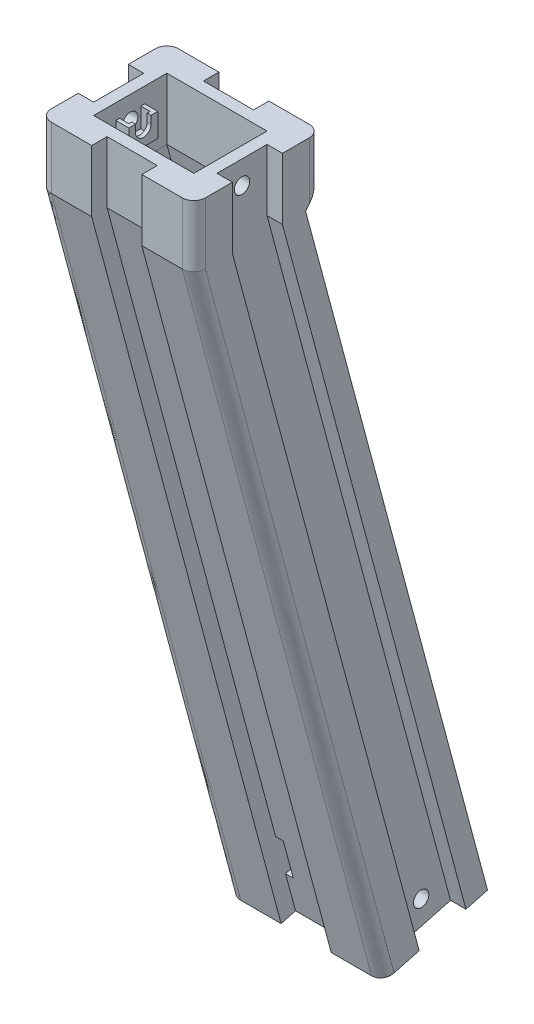
SolidWorks part; units mm, degrees
ref_plane "Front Plane" through (0, 0, 0) normal (0, 0, 1) x (1, 0, 0)
ref_plane "Top Plane" through (0, 0, 0) normal (0, 1, 0) x (1, 0, 0)
ref_plane "Right Plane" through (0, 0, 0) normal (1, 0, 0) x (0, 0, -1)
sketch "Sketch2" plane through (0, 0, 0) normal (0, 1, 0) x (1, 0, 0)
  line L0 (0, 0) -> (0, 33) construction
  line L1 (0, 33) -> (-17, 33)
  line L2 (-20, 30) -> (-20, 3)
  line L3 (-17, 0) -> (0, 0)
  line L4 (-20, 16.5) -> (0, 16.5) construction
  line L5 (0, 33) -> (17, 33)
  line L6 (20, 30) -> (20, 3)
  line L7 (17, 0) -> (0, 0)
  arc A0 (-17, 33) -> (-20, 30) centre (-17, 30) ccw
  arc A1 (-20, 3) -> (-17, 0) centre (-17, 3) ccw
  arc A2 (17, 33) -> (20, 30) centre (17, 30) cw
  arc A3 (20, 3) -> (17, 0) centre (17, 3) cw
  dimension "D3" = 3
  dimension "D1" = 20
  dimension "D2" = 33
extrude "Boss-Extrude1" add sketch "Sketch2" along normal blind 16
sketch "Sketch3" plane through (20, 0, 0) normal (1, 0, 0) x (0, 0, -1)
  line L0 (16.5, 0) -> (16.5, 10) construction
  line L1 (3, 0) -> (30, 0) construction
  circle A0 centre (16.5, 10) radius 2
  dimension "D1" = 4
  dimension "D2" = 10
extrude "Cut-Extrude1" cut sketch "Sketch3" against normal through all
sketch "Sketch14" plane through (0, 16, 0) normal (0, 1, 0) x (1, 0, 0)
  line L0 (17, 33) -> (-17, 33) construction
  line L1 (-6.5, 33) -> (6.5, 33)
  line L2 (-6.5, 33) -> (-6.5, 29)
  line L3 (-6.5, 29) -> (6.5, 29)
  line L4 (6.5, 33) -> (6.5, 29)
  line L5 (20, 3) -> (20, 30) construction
  line L6 (20, 23) -> (16, 23)
  line L7 (20, 23) -> (20, 10)
  line L8 (20, 10) -> (16, 10)
  line L9 (16, 23) -> (16, 10)
  line L10 (-6.5, 29) -> (-6.5, 4) construction
  line L11 (-6.5, 4) -> (-6.5, 0)
  line L12 (-17, 0) -> (17, 0) construction
  line L13 (-6.5, 0) -> (6.5, 0)
  line L14 (6.5, 0) -> (6.5, 4)
  line L15 (6.5, 4) -> (-6.5, 4)
  line L16 (-20, 30) -> (-20, 3) construction
  line L17 (-20, 23) -> (-16, 23)
  line L18 (-20, 23) -> (-20, 10)
  line L19 (-20, 10) -> (-16, 10)
  line L20 (-16, 23) -> (-16, 10)
  line L21 (-16, 23) -> (16, 23) construction
  point P12 (0, 33)
  point P13 (20, 16.5)
  dimension "D1" = 13
  dimension "D2" = 4
extrude "Cut-Extrude12" cut sketch "Sketch14" against normal through all
sketch "Sketch19" plane through (0, 0, 0) normal (0, -1, 0) x (1, 0, 0)
  line L1 (-6.5, -29) -> (6.5, -29) construction
  point P0 (0, -29)
ref_plane "Plane1" through (0, 0, 0) normal (1, 0, 0) x (0, 0, -1)
sketch "Sketch15" plane through (-16, 0, 0) normal (-1, 0, 0) x (0, 0, 1)
  line L0 (-23, 0) -> (-23, 16) construction
  line L1 (-23, -1) -> (-10, -1)
  line L2 (-23, -1) -> (-23, 4)
  line L3 (-23, 4) -> (-10, 4)
  line L4 (-10, -1) -> (-10, 4)
  line L5 (-10, 0) -> (-10, 16) construction
  circle A0 centre (-16.5, 10) radius 2 construction
  dimension "D1" = 5
  dimension "D2" = 6
sketch "Sketch18" plane through (0, 0, 0) normal (1, 0, 0) x (0, 0, -1)
  line L0 (16.5, 0) -> (61.5155, -168)
  line L1 (61.5155, -168) -> (61.5155, 0) construction
  line L2 (61.5155, 0) -> (16.5, 0) construction
  line L4 (4, 0) -> (29, 0) construction
  dimension "D1" = 168
  dimension "D2" = 75
sketch "Sketch20" plane through (0, 0, 0) normal (0, -1, 0) x (1, 0, 0)
  line L0 (20, -23) -> (20, -29)
  line L1 (20, -23) -> (20, -30) construction
  line L2 (20, -29) -> (-20, -29)
  line L3 (-20, -30) -> (-20, -23) construction
  line L4 (-20, -29) -> (-20, -23)
  line L20 (17, 0) -> (6.5, 0)
  line L21 (6.5, 0) -> (6.5, -4)
  line L22 (6.5, -4) -> (-6.5, -4)
  line L23 (-6.5, -4) -> (-6.5, 0)
  line L24 (-6.5, 0) -> (-17, 0)
  line L25 (-20, -3) -> (-20, -10)
  line L26 (-20, -10) -> (-16, -10)
  line L27 (-16, -10) -> (-16, -23)
  line L28 (-16, -23) -> (-20, -23)
  line L29 (-20, -23) -> (-20, -30)
  line L30 (-17, -33) -> (-6.5, -33)
  line L31 (-6.5, -33) -> (-6.5, -29)
  line L32 (-6.5, -29) -> (6.5, -29)
  line L33 (6.5, -29) -> (6.5, -33)
  line L34 (6.5, -33) -> (17, -33)
  line L35 (20, -30) -> (20, -23)
  line L36 (20, -23) -> (16, -23)
  line L37 (16, -23) -> (16, -10)
  line L38 (16, -10) -> (20, -10)
  line L39 (20, -10) -> (20, -3)
  line L40 (17, 0) -> (6.5, 0)
  line L41 (6.5, 0) -> (6.5, -4)
  line L42 (6.5, -4) -> (-6.5, -4)
  line L43 (-6.5, -4) -> (-6.5, 0)
  line L44 (-6.5, 0) -> (-17, 0)
  line L45 (-20, -3) -> (-20, -10)
  line L46 (-20, -10) -> (-16, -10)
  line L47 (-16, -10) -> (-16, -23)
  line L48 (-16, -23) -> (-20, -23)
  line L56 (20, -23) -> (16, -23)
  line L57 (16, -23) -> (16, -10)
  line L58 (16, -10) -> (20, -10)
  line L59 (20, -10) -> (20, -3)
  arc A4 (-17, 0) -> (-20, -3) centre (-17, -3) ccw
  arc A5 (-20, -30) -> (-17, -33) centre (-17, -30) ccw
  arc A6 (17, -33) -> (20, -30) centre (17, -30) ccw
  arc A7 (20, -3) -> (17, 0) centre (17, -3) ccw
  arc A8 (-17, 0) -> (-20, -3) centre (-17, -3) ccw
  arc A11 (20, -3) -> (17, 0) centre (17, -3) ccw
  dimension "D1" = 0
sweep "Sweep1" add profiles "Sketch20" path "Sketch18"
sketch "Sketch24" plane through (0, 0, 0) normal (1, 0, 0) x (0, 0, -1)
  line L0 (45.0155, -168) -> (74.0155, -168)
  line L1 (74.0155, -168) -> (74.0155, -160.2295)
  line L2 (74.0155, -160.2295) -> (45.0155, -168)
  line L3 (55.0155, -168) -> (10, 0) construction
extrude "Cut-Extrude17" cut sketch "Sketch24" against normal through all both and the other way through all
sketch "Sketch22" plane through (0, -175.667, -16.4019) normal (0, -0.9659, -0.2588) x (1, 0, 0)
  line L7 (20, -39.2822) -> (16, -39.2822) construction
  line L8 (20, -32.5207) -> (20, -39.2822) construction
  line L9 (17, -29.6229) -> (6.5, -29.6229) construction
  line L10 (6.5, -33.4866) -> (6.5, -29.6229) construction
  line L11 (-6.5, -33.4866) -> (6.5, -33.4866) construction
  line L12 (-6.5, -29.6229) -> (-6.5, -33.4866) construction
  line L13 (-6.5, -29.6229) -> (-17, -29.6229) construction
  line L14 (-20, -39.2822) -> (-20, -32.5207) construction
  line L15 (-20, -39.2822) -> (-16, -39.2822) construction
  line L16 (20, -39.2822) -> (16, -39.2822)
  line L17 (20, -32.5207) -> (20, -39.2822)
  line L18 (17, -29.6229) -> (6.5, -29.6229)
  line L19 (6.5, -33.4866) -> (6.5, -29.6229)
  line L20 (-6.5, -33.4866) -> (6.5, -33.4866)
  line L21 (-6.5, -29.6229) -> (-6.5, -33.4866)
  line L22 (-6.5, -29.6229) -> (-17, -29.6229)
  line L23 (-20, -39.2822) -> (-20, -32.5207)
  line L24 (-20, -39.2822) -> (-16, -39.2822)
  line L25 (-16, -39.2822) -> (-16, -51.8392)
  line L26 (-16, -51.8392) -> (-16, -39.2822) construction
  line L27 (-16, -45.5607) -> (16, -45.5607) construction
  line L28 (16, -39.2822) -> (16, -51.8392) construction
  line L29 (16, -51.8392) -> (16, -39.2822)
  line L30 (-20, -51.8392) -> (-16, -51.8392)
  line L31 (-20, -51.8392) -> (-20, -58.6007) construction
  line L32 (-6.5, -61.4985) -> (-17, -61.4985) construction
  line L33 (-6.5, -61.4985) -> (-6.5, -57.6348) construction
  line L34 (-6.5, -57.6348) -> (6.5, -57.6348) construction
  line L35 (6.5, -57.6348) -> (6.5, -61.4985) construction
  line L36 (17, -61.4985) -> (6.5, -61.4985) construction
  line L37 (20, -58.6007) -> (20, -51.8392) construction
  line L38 (20, -51.8392) -> (16, -51.8392)
  line L39 (-20, -51.8392) -> (-20, -57.6348)
  line L40 (-20, -57.6348) -> (20, -57.6348)
  line L41 (20, -57.6348) -> (20, -51.8392)
  spline S0 degree 3 poles (17, -29.6229) (18.7574, -29.6229) (20, -30.8232) (20, -32.5207) knots 0 0 0 0 1 1 1 1 weights 1 0.804738 0.804738 1 construction
  spline S1 degree 3 poles (-20, -32.5207) (-20, -30.8232) (-18.7574, -29.6229) (-17, -29.6229) knots 0 0 0 0 1 1 1 1 weights 1 0.804738 0.804738 1 construction
  spline S2 degree 3 poles (17, -29.6229) (18.7574, -29.6229) (20, -30.8232) (20, -32.5207) knots 0 0 0 0 1 1 1 1 weights 1 0.804738 0.804738 1
  spline S3 degree 3 poles (-20, -32.5207) (-20, -30.8232) (-18.7574, -29.6229) (-17, -29.6229) knots 0 0 0 0 1 1 1 1 weights 1 0.804738 0.804738 1
  spline S4 degree 3 poles (-20, -58.6007) (-20, -60.2982) (-18.7574, -61.4985) (-17, -61.4985) knots 0 0 0 0 1 1 1 1 weights 1 0.804738 0.804738 1 construction
  spline S5 degree 3 poles (17, -61.4985) (18.7574, -61.4985) (20, -60.2982) (20, -58.6007) knots 0 0 0 0 1 1 1 1 weights 1 0.804738 0.804738 1 construction
extrude "Boss-Extrude2" add sketch "Sketch22" along normal blind 16
sketch "Sketch23" plane through (-16, 0, 0) normal (-1, 0, 0) x (0, 0, 1)
  line L0 (-62.9984, -173.5343) -> (-64.5513, -179.3298) construction
  line L3 (-58.4867, -180.9548) -> (-70.6159, -177.7048) construction
  line L4 (-62.9984, -173.5343) -> (-60.4102, -163.875) construction
  circle A0 centre (-62.9984, -173.5343) radius 2
  dimension "D2" = 4
  dimension "D1" = 10
  dimension "D3" = 6
extrude "Cut-Extrude16" cut sketch "Sketch23" against normal through all
sketch "Sketch25" plane through (0, 16, 0) normal (0, 1, 0) x (1, 0, 0)
  line L0 (0, 4) -> (0, 7) construction
  line L1 (13, 7) -> (-13, 7)
  line L2 (13, 7) -> (13, 26)
  line L3 (13, 26) -> (-13, 26)
  line L4 (-13, 7) -> (-13, 26)
  line L5 (6.5, 4) -> (-6.5, 4) construction
  line L6 (16, 16.5) -> (13, 16.5) construction
  line L7 (16, 23) -> (16, 10) construction
  dimension "D1" = 3
extrude "Cut-Extrude18" cut sketch "Sketch25" against normal blind 16
sketch "Sketch26" plane through (0, 0, 0) normal (0, 1, 0) x (1, 0, 0)
  line L4 (13, 7) -> (13, 26)
  line L5 (13, 26) -> (-13, 26)
  line L6 (-13, 26) -> (-13, 7)
  line L7 (-13, 7) -> (13, 7)
  line L8 (13, 7) -> (13, 26)
  line L9 (13, 26) -> (-13, 26)
  line L10 (-13, 26) -> (-13, 7)
  line L11 (-13, 7) -> (13, 7)
  dimension "D1" = 0
sketch "Sketch27" plane through (0, -183.4548, -49.1566) normal (0, -0.9659, -0.2588) x (1, 0, 0)
  line L0 (0, -3.8637) -> (0, -6.7615) construction
  line L1 (-13.1022, -6.7615) -> (13.1022, -6.7615)
  line L2 (-13.1022, -6.7615) -> (-13.1022, -25.1141)
  line L3 (-13.1022, -25.1141) -> (13.1022, -25.1141)
  line L4 (13.1022, -6.7615) -> (13.1022, -25.1141)
  line L5 (6.5, -3.8637) -> (-6.5, -3.8637) construction
  line L6 (-13.1022, -15.9378) -> (-16, -15.9378) construction
  line L7 (-16, -9.6593) -> (-16, -22.2163) construction
  line L8 (0, -8.0048) -> (0, -10.9026) construction
loft "Cut-Loft1" cut profiles "Sketch27", "Sketch26"
sketch "Sketch29" plane through (0, 0, 0) normal (1, 0, 0) x (0, 0, -1)
  line L0 (29, 0) -> (33, 4.767)
  line L1 (33, 4.767) -> (33, 0)
  line L2 (33, 0) -> (29, 0)
  line L3 (33, 16) -> (33, 0) construction
  dimension "D1" = 50
extrude "Cut-Extrude19" cut sketch "Sketch29" against normal through all both and the other way through all
sketch "Sketch30" plane through (-16, 0, 0) normal (-1, 0, 0) x (0, 0, 1)
  line L0 (-23, 0) -> (-20.5, 0) construction
  line L1 (-20.5, -2) -> (-12.5, -2)
  line L2 (-20.5, -2) -> (-20.5, 5)
  line L3 (-20.5, 5) -> (-12.5, 5)
  line L4 (-12.5, -2) -> (-12.5, 5)
  line L5 (-20.5, 0) -> (-12.5, 0) construction
  line L6 (-12.5, 0) -> (-10, 0) construction
  circle A0 centre (-16.5, 10) radius 2 construction
  dimension "D1" = 8
  dimension "D2" = 7
  dimension "D3" = 5
extrude "Cut-Extrude20" cut sketch "Sketch30" against normal blind 10
sketch "Sketch31" plane through (-13, 0, 0) normal (1, 0, 0) x (0, 0, -1)
  line L0 (13.75, 12) -> (13.75, 6.9)
  line L1 (13.75, 6.9) -> (19.25, 6.9)
  line L2 (19.25, 6.9) -> (19.25, 12)
  line L3 (19.25, 12) -> (20.25, 12)
  line L4 (20.25, 12) -> (20.25, 5.9)
  line L5 (20.25, 5.9) -> (12.75, 5.9)
  line L6 (12.75, 5.9) -> (12.75, 12)
  line L7 (12.75, 12) -> (13.75, 12)
  line L8 (19.25, 12) -> (13.75, 12) construction
  line L9 (16.5, 6.9) -> (16.5, 5.9) construction
  circle A0 centre (16.5, 10) radius 2 construction
  point P10 (16.5, 12)
  point P11 (16.5, 10)
  dimension "D1" = 5.5
  dimension "D2" = 3.1
  dimension "D3" = 1
extrude "Boss-Extrude5" add sketch "Sketch31" along normal blind 2.4
sketch "Sketch34" plane through (13, 0, 0) normal (-1, 0, 0) x (0, 0, 1)
  line L8 (-12.75, 12) -> (-13.75, 12)
  line L9 (-12.75, 5.9) -> (-12.75, 12)
  line L10 (-20.25, 5.9) -> (-12.75, 5.9)
  line L11 (-20.25, 12) -> (-20.25, 5.9)
  line L12 (-19.25, 12) -> (-20.25, 12)
  line L13 (-19.25, 6.9) -> (-19.25, 12)
  line L14 (-13.75, 6.9) -> (-19.25, 6.9)
  line L15 (-13.75, 12) -> (-13.75, 6.9)
  line L16 (-12.75, 12) -> (-13.75, 12)
  line L17 (-12.75, 5.9) -> (-12.75, 12)
  line L18 (-20.25, 5.9) -> (-12.75, 5.9)
  line L19 (-20.25, 12) -> (-20.25, 5.9)
  line L20 (-19.25, 12) -> (-20.25, 12)
  line L21 (-19.25, 6.9) -> (-19.25, 12)
  line L22 (-13.75, 6.9) -> (-19.25, 6.9)
  line L23 (-13.75, 12) -> (-13.75, 6.9)
  dimension "D1" = 0
extrude "Boss-Extrude6" add sketch "Sketch34" along normal blind 2.4
sketch "Sketch35" plane through (-10.6, 0, 0) normal (1, 0, 0) x (0, 0, -1)
  line L0 (12.75, 12) -> (14.5, 12)
  line L1 (12.75, 12) -> (20.25, 12) construction
  line L2 (12.75, 12) -> (12.75, 5.9)
  line L3 (12.75, 5.9) -> (20.25, 5.9)
  line L4 (20.25, 12) -> (20.25, 5.9)
  line L5 (14.5, 12) -> (14.5, 10)
  line L6 (18.5, 10) -> (18.5, 12)
  line L7 (18.5, 12) -> (20.25, 12)
  arc A0 (14.5, 10) -> (18.5, 10) centre (16.5, 10) ccw
  circle A1 centre (16.5, 10) radius 2 construction
extrude "Boss-Extrude7" add sketch "Sketch35" along normal blind 1
sketch "Sketch36" plane through (10.6, 0, 0) normal (-1, 0, 0) x (0, 0, 1)
  line L7 (-12.75, 5.9) -> (-12.75, 12)
  line L8 (-20.25, 5.9) -> (-12.75, 5.9)
  line L9 (-20.25, 12) -> (-20.25, 5.9)
  line L10 (-18.5, 12) -> (-20.25, 12)
  line L11 (-18.5, 10) -> (-18.5, 12)
  line L12 (-14.5, 12) -> (-14.5, 10)
  line L13 (-12.75, 12) -> (-14.5, 12)
  line L14 (-12.75, 5.9) -> (-12.75, 12)
  line L15 (-20.25, 5.9) -> (-12.75, 5.9)
  line L16 (-20.25, 12) -> (-20.25, 5.9)
  line L17 (-18.5, 12) -> (-20.25, 12)
  line L18 (-18.5, 10) -> (-18.5, 12)
  line L19 (-14.5, 12) -> (-14.5, 10)
  line L20 (-12.75, 12) -> (-14.5, 12)
  arc A1 (-18.5, 10) -> (-14.5, 10) centre (-16.5, 10) ccw
  arc A2 (-18.5, 10) -> (-14.5, 10) centre (-16.5, 10) ccw
  dimension "D1" = 0
extrude "Boss-Extrude8" add sketch "Sketch36" along normal blind 1
sketch "Sketch37" plane through (0, -183.4548, -49.1566) normal (0, -0.9659, -0.2588) x (1, 0, 0)
  line L0 (13.1022, -25.1141) -> (13.1022, -6.7615) construction
  line L1 (13.1022, -19.6878) -> (9.7022, -19.6878)
  line L2 (13.1022, -19.6878) -> (13.1022, -12.1878)
  line L3 (13.1022, -12.1878) -> (9.7022, -12.1878)
  line L4 (9.7022, -19.6878) -> (9.7022, -12.1878)
  line L5 (-13.1022, -6.7615) -> (-13.1022, -25.1141) construction
  line L6 (-9.7022, -19.6878) -> (-13.1022, -19.6878)
  line L7 (-9.7022, -19.6878) -> (-9.7022, -12.1878)
  line L8 (-9.7022, -12.1878) -> (-13.1022, -12.1878)
  line L9 (-13.1022, -19.6878) -> (-13.1022, -12.1878)
  line L10 (9.7022, -12.1878) -> (-9.7022, -12.1878) construction
  line L11 (9.7022, -19.6878) -> (-9.7022, -19.6878) construction
  point P6 (13.1022, -15.9378)
  point P7 (13.1022, -15.9378)
  dimension "D1" = 3.4
  dimension "D2" = 7.5
extrude "Boss-Extrude9" add sketch "Sketch37" against normal blind 8.2
sketch "Sketch38" plane through (0, -175.5342, -47.0343) normal (0, 0.9659, 0.2588) x (1, 0, 0)
  line L0 (-13.0977, 19.6878) -> (-13.0977, 12.1878) construction
  line L1 (-13.0977, 18.6878) -> (-10.6977, 18.6878)
  line L2 (-13.0977, 18.6878) -> (-13.0977, 13.1878)
  line L3 (-13.0977, 13.1878) -> (-10.6977, 13.1878)
  line L4 (-10.6977, 18.6878) -> (-10.6977, 13.1878)
  line L5 (13.0977, 12.1878) -> (13.0977, 19.6878) construction
  line L6 (13.0977, 18.6878) -> (10.6977, 18.6878)
  line L7 (13.0977, 18.6878) -> (13.0977, 13.1878)
  line L8 (13.0977, 13.1878) -> (10.6977, 13.1878)
  line L9 (10.6977, 18.6878) -> (10.6977, 13.1878)
  line L10 (-10.6977, 15.9378) -> (-9.7022, 15.9378) construction
  line L11 (-9.7022, 19.6878) -> (-9.7022, 12.1878) construction
  dimension "D1" = 2.4
  dimension "D2" = 5.5
extrude "Cut-Extrude21" cut sketch "Sketch38" against normal blind 5.3
sketch "Sketch40" plane through (9.7022, 0, 0) normal (-1, 0, 0) x (0, 0, 1)
  circle A0 centre (-62.9984, -173.5343) radius 2
  circle A2 centre (-62.9984, -173.5343) radius 2 construction
extrude "Cut-Extrude26" cut sketch "Sketch40" against normal through all both and the other way through all
sketch "Sketch41" plane through (9.7022, 0, 0) normal (-1, 0, 0) x (0, 0, 1)
  line L0 (-64.9302, -173.0166) -> (-64.3608, -170.8916)
  line L1 (-58.8067, -172.3798) -> (-66.0512, -170.4387) construction
  line L2 (-64.3608, -170.8916) -> (-60.4971, -171.9269)
  line L3 (-60.4971, -171.9269) -> (-61.0665, -174.0519)
  line L4 (-61.0665, -174.0519) -> (-64.9302, -173.0166)
  circle A0 centre (-62.9984, -173.5343) radius 2 construction
extrude "Cut-Extrude27" cut sketch "Sketch41" against normal blind 2 and the other way blind 21
sketch "Sketch42" plane through (-16, 0, 0) normal (-1, 0, 0) x (0, 0, 1)
  line L0 (-55.8985, -171.2956) -> (-53.3103, -161.6363)
  line L1 (-58.4867, -180.9548) -> (-10, 0) construction
  line L2 (-53.3103, -161.6363) -> (-55.2422, -161.1187)
  line L3 (-55.2422, -161.1187) -> (-57.8304, -170.7779)
  line L4 (-57.8304, -170.7779) -> (-55.8985, -171.2956)
  line L5 (-58.4867, -180.9548) -> (-70.6159, -177.7048) construction
  dimension "D1" = 2
  dimension "D2" = 10
  dimension "D3" = 10
extrude "Cut-Extrude28" cut sketch "Sketch42" against normal blind 5
sketch "Sketch43" plane through (0, 1, -3.7321) normal (0, -0.2588, 0.9659) x (1, 0, 0)
  line L0 (-6.5, -169.9264) -> (-6.5, -179.9264)
  line L1 (-6.5, -189.9264) -> (-6.5, -1.0353) construction
  line L2 (-6.5, -179.9264) -> (-4.5, -179.9264)
  line L3 (-4.5, -179.9264) -> (-4.5, -169.9264)
  line L4 (-4.5, -169.9264) -> (-6.5, -169.9264)
  line L5 (6.5, -1.0353) -> (6.5, -11.0353)
  line L6 (6.5, -189.9264) -> (6.5, -1.0353) construction
  line L7 (6.5, -11.0353) -> (4.5, -11.0353)
  line L8 (4.5, -11.0353) -> (4.5, -1.0353)
  line L9 (6.5, -1.0353) -> (-6.5, -1.0353) construction
  line L10 (4.5, -1.0353) -> (6.5, -1.0353)
  dimension "D1" = 2
extrude "Cut-Extrude29" cut sketch "Sketch43" against normal blind 5
sketch "Sketch44" plane through (16, 0, 0) normal (1, 0, 0) x (0, 0, -1)
  line L0 (10, 0) -> (12.5882, -9.6593)
  line L1 (58.4867, -180.9548) -> (10, 0) construction
  line L2 (10, 0) -> (10, 16) construction
  line L3 (12.5882, -9.6593) -> (14.52, -9.1416)
  line L4 (14.52, -9.1416) -> (11.9319, 0.5176)
  line L5 (11.9319, 0.5176) -> (10, 0)
  dimension "D1" = 10
  dimension "D2" = 2
extrude "Cut-Extrude30" cut sketch "Sketch44" against normal blind 5
